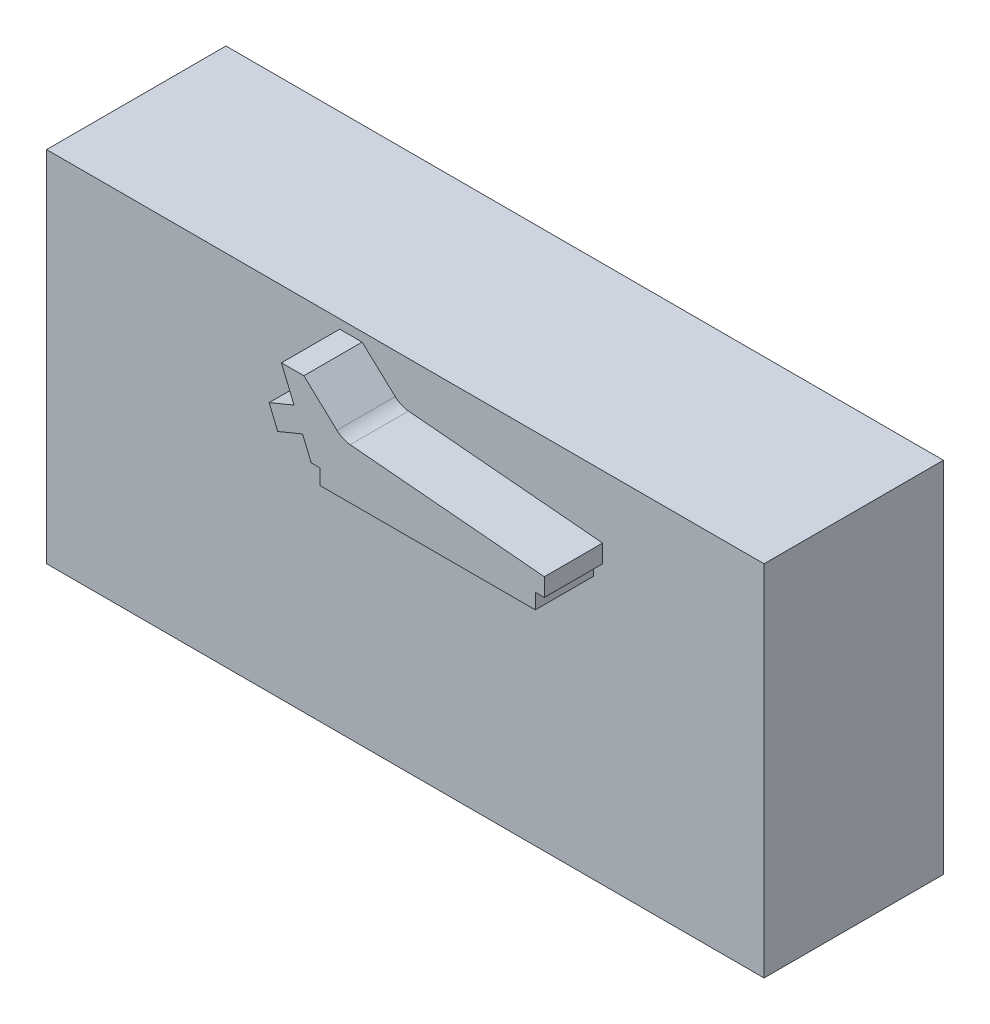
SolidWorks part; units mm, degrees
ref_plane "Plane1" through (0, 0, 0) normal (0, 0, 1) x (1, 0, 0)
ref_plane "Plane2" through (0, 0, 0) normal (0, 1, 0) x (1, 0, 0)
ref_plane "Plane3" through (0, 0, 0) normal (1, 0, 0) x (0, 0, -1)
sketch "Sketch1" plane through (0, 0, 0) normal (0, 0, 1) x (1, 0, 0)
  line L1 (0, 0) -> (203.2, 0)
  line L2 (0, 0) -> (0, 101.6)
  line L3 (0, 101.6) -> (203.2, 101.6)
  line L4 (203.2, 0) -> (203.2, 101.6)
  dimension "D1" = 203.2
  dimension "D2" = 101.6
extrude "Extrude1" add sketch "Sketch1" along normal blind 50.8
sketch "Sketch2" plane through (0, 0, 50.8) normal (0, 0, 1) x (1, 0, 0)
  line L0 (83.0232, 99.06) -> (89.3732, 99.06)
  line L2 (157.48, 83.82) -> (157.48, 78.74)
  line L3 (157.48, 78.74) -> (91.44, 78.74)
  line L4 (91.44, 78.74) -> (83.0232, 99.06)
  line L5 (203.2, 101.6) -> (0, 101.6) construction
  line L6 (0, 101.6) -> (0, 0) construction
  line L7 (157.48, 83.82) -> (102.4931, 88.7077)
  line L8 (98.7377, 90.3765) -> (89.3732, 99.06)
  arc A0 (98.7377, 90.3765) -> (102.4931, 88.7077) centre (103.0553, 95.0328) ccw
  point P12 (100.33, 88.9)
  dimension "D10" = 6.35
  dimension "D1" = 67.5
  dimension "D2" = 20.32
  dimension "D3" = 2.54
  dimension "D4" = 5.08
  dimension "D5" = 66.04
  dimension "D6" = 157.48
  dimension "D7" = 6.35
  dimension "D8" = 57.15
  dimension "D9" = 5.08
sketch "Sketch4" plane through (0, 0, 50.8) normal (0, 0, 1) x (1, 0, 0)
  line L0 (86.5799, 90.4733) -> (72.5, 84.6412)
  line L1 (91.44, 78.74) -> (83.0232, 99.06) construction
  line L2 (72.5, 84.6412) -> (69.6673, 84.8425)
  line L3 (69.6673, 84.8425) -> (73.0694, 76.6292)
  line L4 (73.0694, 76.6292) -> (74.93, 78.7745)
  line L5 (74.93, 78.7745) -> (89.01, 84.6066)
  line L6 (89.01, 84.6066) -> (91.8426, 84.4053)
  line L7 (91.8426, 84.4053) -> (88.4406, 92.6186)
  line L8 (88.4406, 92.6186) -> (86.5799, 90.4733)
  dimension "D1" = 6.35
  dimension "D2" = 8.89
  dimension "D3" = 1.27
  dimension "D4" = 8.89
  dimension "D5" = 1.27
  dimension "D6" = 2.54
  dimension "D7" = 2.54
  dimension "D8" = 15.24
  dimension "D9" = 6.35
sketch "Sketch5" plane through (0, 0, 50.8) normal (0, 0, 1) x (1, 0, 0)
  line L0 (69.7842, 91.1978) -> (77.5603, 72.4245)
  line L1 (77.5603, 72.4245) -> (43.4353, 38.2996)
  line L2 (43.4353, 38.2996) -> (23.4233, 51.0486)
  line L5 (23.4233, 51.0486) -> (30.1436, 56.8684)
  line L6 (157.48, 78.74) -> (91.44, 78.74) construction
  line L7 (30.1436, 56.8684) -> (37.6275, 52.1007)
  line L8 (45.5295, 52.9661) -> (64.4212, 71.8578)
  line L9 (65.7977, 78.778) -> (63.0639, 85.3779)
  line L10 (63.0639, 85.3779) -> (69.7842, 91.1978)
  arc A0 (37.6275, 52.1007) -> (45.5295, 52.9661) centre (41.0393, 57.4562) ccw
  arc A1 (65.7977, 78.778) -> (64.4212, 71.8578) centre (59.9311, 76.3479) cw
  point P14 (41.9258, 49.3624)
  dimension "D10" = 6.35
  dimension "D1" = 135
  dimension "D2" = 6.35
  dimension "D3" = 8.89
  dimension "D4" = 48.26
  dimension "D5" = 102.5
  dimension "D6" = 8.89
  dimension "D7" = 20.32
  dimension "D8" = 8.89
  dimension "D9" = 13.97
sketch "Sketch6" plane through (0, 0, 50.8) normal (0, 0, 1) x (1, 0, 0)
  line L0 (31.6531, 45.8056) -> (23.4647, 32.9524)
  line L1 (43.4353, 38.2996) -> (23.4233, 51.0486) construction
  line L2 (23.4647, 32.9524) -> (21.0288, 31.4925)
  line L3 (21.0288, 31.4925) -> (26.3844, 28.0807)
  line L4 (26.3844, 28.0807) -> (26.678, 30.9052)
  line L5 (26.678, 30.9052) -> (34.8665, 43.7585)
  line L6 (34.8665, 43.7585) -> (37.3023, 45.2184)
  line L7 (37.3023, 45.2184) -> (31.9468, 48.6302)
  line L9 (31.9468, 48.6302) -> (31.6531, 45.8056)
  dimension "D1" = 3.81
  dimension "D2" = 6.35
  dimension "D3" = 6.35
  dimension "D4" = 1.27
  dimension "D5" = 1.27
  dimension "D6" = 2.54
  dimension "D7" = 2.54
  dimension "D8" = 15.24
  dimension "D9" = 10.16
sketch "Sketch8" plane through (0, 0, 50.8) normal (0, 0, 1) x (1, 0, 0)
  line L0 (16.648, 37.2951) -> (33.1047, 26.811)
  line L1 (33.1047, 26.811) -> (26.5892, 8.9099)
  line L2 (26.5892, 8.9099) -> (2.721, 17.5972)
  line L3 (16.648, 37.2951) -> (10.6809, 39.4669)
  line L4 (2.721, 17.5972) -> (10.6809, 39.4669)
  line L8 (43.4353, 38.2996) -> (23.4233, 51.0486) construction
  dimension "D1" = 7.62
  dimension "D2" = 102.5
  dimension "D3" = 25.4
  dimension "D4" = 19.05
  dimension "D5" = 6.35
sketch "Sketch14" plane through (0, 0, 50.8) normal (0, 0, 1) x (1, 0, 0)
  line L0 (157.48, 78.74) -> (91.44, 78.74) construction
  line L1 (93.98, 80.772) -> (154.94, 80.772)
  line L2 (93.98, 80.772) -> (93.98, 74.422)
  line L3 (93.98, 74.422) -> (154.94, 74.422)
  line L4 (154.94, 80.772) -> (154.94, 74.422)
  line L5 (157.48, 83.82) -> (157.48, 78.74) construction
  dimension "D1" = 2.032
  dimension "D2" = 2.54
  dimension "D3" = 2.54
  dimension "D4" = 6.35
sketch "Sketch15" plane through (0, 0, 50.8) normal (0, 0, 1) x (1, 0, 0)
  line L0 (43.7945, 41.5325) -> (48.2847, 37.0423)
  line L2 (48.2847, 37.0423) -> (78.8175, 67.5752)
  line L3 (78.8175, 67.5752) -> (74.3274, 72.0653)
  line L4 (74.3274, 72.0653) -> (43.7945, 41.5325)
  line L5 (77.5603, 72.4245) -> (43.4353, 38.2996) construction
  dimension "D1" = 2.032
  dimension "D2" = 2.54
  dimension "D3" = 6.35
  dimension "D4" = 2.54
sketch "Sketch16" plane through (0, 0, 50.8) normal (0, 0, 1) x (1, 0, 0)
  line L0 (25.5485, 11.9917) -> (31.5155, 9.8199)
  line L1 (31.5155, 9.8199) -> (36.2935, 22.9474)
  line L2 (36.2935, 22.9474) -> (30.3265, 25.1192)
  line L3 (30.3265, 25.1192) -> (25.5485, 11.9917)
  line L4 (33.1047, 26.811) -> (26.5892, 8.9099) construction
  dimension "D1" = 2.032
  dimension "D2" = 6.35
  dimension "D3" = 2.54
  dimension "D4" = 2.54
sketch "Sketch19" plane through (0, 0, 50.8) normal (0, 0, 1) x (1, 0, 0)
  line L0 (155.194, 72.39) -> (86.506, 72.39)
  line L1 (86.506, 72.39) -> (45.2314, 31.1154)
  line L2 (45.2314, 31.1154) -> (113.9194, 31.1154)
  line L3 (113.9194, 31.1154) -> (155.194, 72.39)
  line L4 (93.98, 74.422) -> (154.94, 74.422) construction
  line L5 (48.2847, 37.0423) -> (78.8175, 67.5752) construction
  line L7 (43.7945, 41.5325) -> (48.2847, 37.0423) construction
  line L8 (154.94, 80.772) -> (154.94, 74.422) construction
  dimension "D1" = 2.032
  dimension "D2" = 2.032
  dimension "D3" = 6.35
  dimension "D4" = 0.254
sketch "Sketch20" plane through (0, 0, 50.8) normal (0, 0, 1) x (1, 0, 0)
  line L0 (79.54, 87.5572) -> (81.97, 81.6906)
  line L1 (86.5799, 90.4733) -> (72.5, 84.6412) construction
  line L3 (81.97, 81.6906) -> (89.01, 84.6066)
  line L4 (89.01, 84.6066) -> (91.44, 78.74)
  line L5 (79.54, 87.5572) -> (86.5799, 90.4733)
  line L6 (86.5799, 90.4733) -> (83.0232, 99.06)
  line L7 (157.48, 78.74) -> (91.44, 78.74) construction
  line L8 (93.98, 80.772) -> (93.98, 74.422) construction
  line L9 (91.44, 78.74) -> (93.98, 78.74)
  line L10 (93.98, 78.74) -> (93.98, 74.422)
  line L11 (93.98, 74.422) -> (154.94, 74.422)
  line L12 (154.94, 74.422) -> (154.94, 78.74)
  line L13 (154.94, 80.772) -> (154.94, 74.422) construction
  line L14 (154.94, 78.74) -> (157.48, 78.74)
  line L15 (157.48, 78.74) -> (157.48, 83.82)
  line L16 (157.48, 83.82) -> (102.4931, 88.7077)
  line L17 (98.7377, 90.3765) -> (89.3732, 99.06)
  line L18 (89.3732, 99.06) -> (83.0232, 99.06)
  arc A1 (98.7377, 90.3765) -> (102.4931, 88.7077) centre (103.0553, 95.0328) ccw
  arc A3 (98.7377, 90.3765) -> (102.4931, 88.7077) centre (103.0553, 95.0328) ccw construction
  point P16 (93.98, 78.74)
extrude "Extrude2" add sketch "Sketch20" along normal blind 16.51 contours A1 L17 L18 L6 L5 L0 L3 L4 L9 L10 L11 L12 L14 L15 L16
